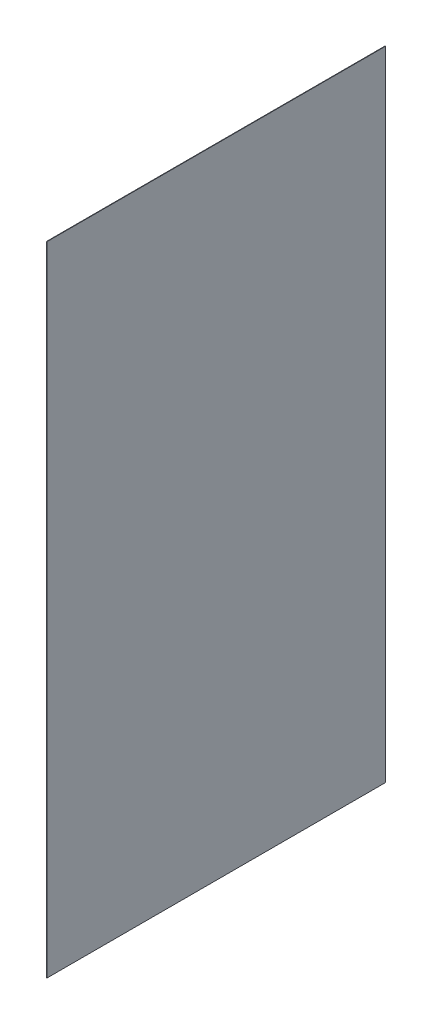
SolidWorks part; units mm, degrees
ref_plane "Front Plane" through (0, 0, 0) normal (0, 0, 1) x (1, 0, 0)
ref_plane "Top Plane" through (0, 0, 0) normal (0, 1, 0) x (1, 0, 0)
ref_plane "Right Plane" through (0, 0, 0) normal (1, 0, 0) x (0, 0, -1)
other "Configuration Table"
sketch "Sketch1" plane through (0, 0, 0) normal (0, 0, 1) x (1, 0, 0)
  line L1 (713, 182.5) -> (714, 182.5)
  line L2 (713, 182.5) -> (713, 1610)
  line L3 (713, 1610) -> (714, 1610)
  line L4 (714, 182.5) -> (714, 1610)
extrude "STORE_orta_bolme_sac_sag_1" add sketch "Sketch1" against normal blind 757.5 separate body
